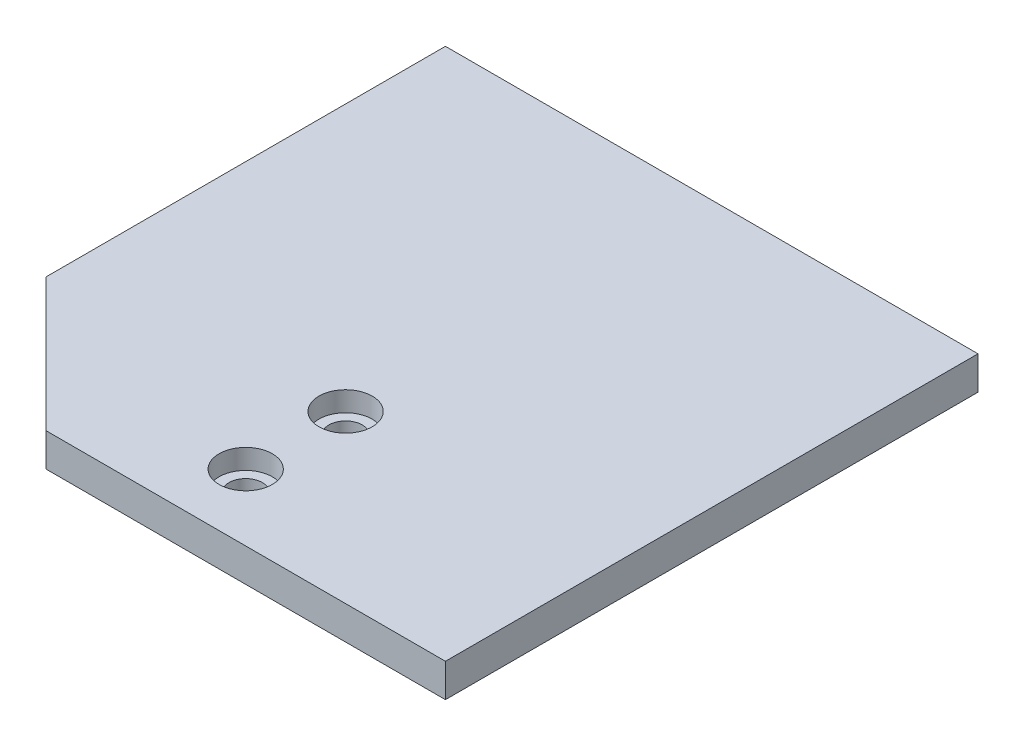
SolidWorks part; units mm, degrees
ref_plane "Front Plane" through (0, 0, 0) normal (0, 0, 1) x (1, 0, 0)
ref_plane "Top Plane" through (0, 0, 0) normal (0, 1, 0) x (1, 0, 0)
ref_plane "Right Plane" through (0, 0, 0) normal (1, 0, 0) x (0, 0, -1)
sketch "Sketch1" plane through (0, 0, 0) normal (0, 1, 0) x (1, 0, 0)
  line L1 (40, -40) -> (-20, -40)
  line L2 (40, -40) -> (40, 40)
  line L3 (40, 40) -> (-40, 40)
  line L4 (-40, -20) -> (-40, 40)
  line L5 (40, -40) -> (-40, 40) construction
  line L6 (40, 40) -> (-30, -30) construction
  line L8 (-20, -40) -> (-40, -20)
  point P0 (0, 0)
extrude "Boss-Extrude1" add sketch "Sketch1" along normal blind 5
sketch "Sketch2" plane through (0, 5, 0) normal (0, 1, 0) x (1, 0, 0)
  circle A0 centre (0, -15) radius 2.5
  circle A1 centre (0, -30) radius 2.5
extrude "Cut-Extrude1" cut sketch "Sketch2" against normal blind 15
sketch "Sketch3" plane through (0, 5, 0) normal (0, 1, 0) x (1, 0, 0)
  circle A0 centre (0, -15) radius 4
  circle A1 centre (0, -30) radius 4
extrude "Cut-Extrude2" cut sketch "Sketch3" against normal blind 3
